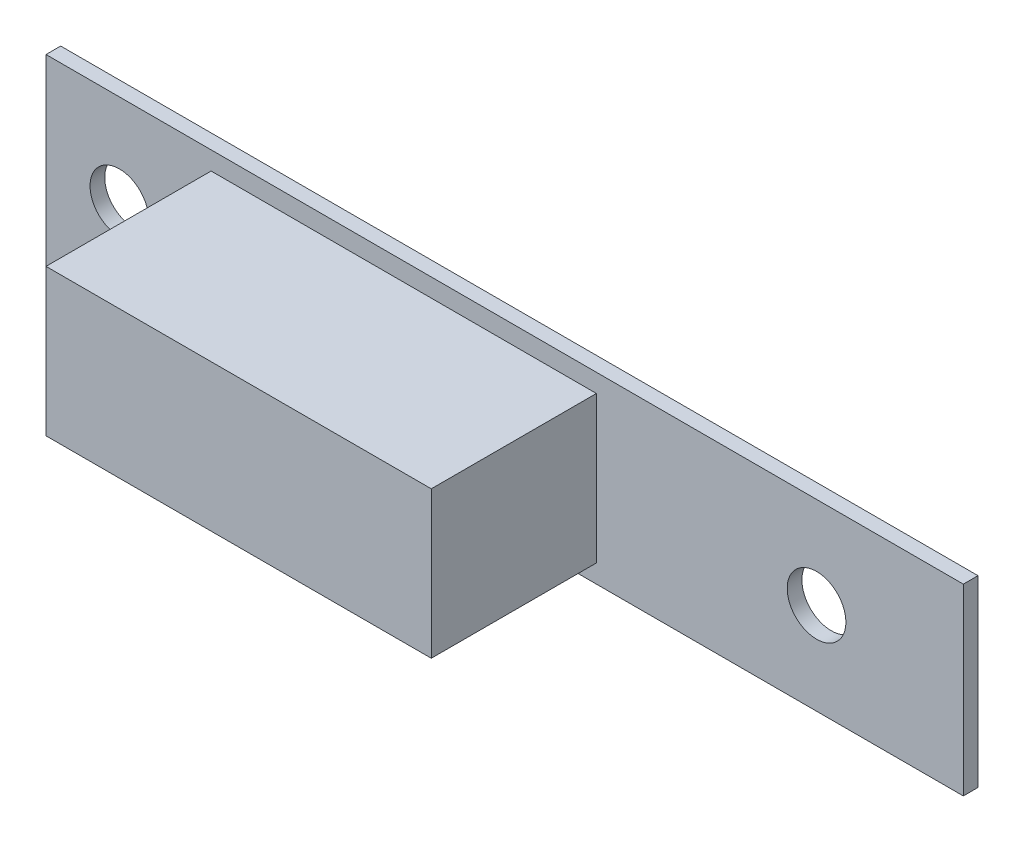
SolidWorks part; units mm, degrees
ref_plane "Front Plane" through (0, 0, 0) normal (0, 0, 1) x (1, 0, 0)
ref_plane "Top Plane" through (0, 0, 0) normal (0, 1, 0) x (1, 0, 0)
ref_plane "Right Plane" through (0, 0, 0) normal (1, 0, 0) x (0, 0, -1)
sketch "Sketch1" plane through (0, 0, 0) normal (0, 0, 1) x (1, 0, 0)
  line L0 (0, 5) -> (50000, 5) construction
  line L1 (0, 0) -> (50, 0)
  line L2 (0, 0) -> (0, 10)
  line L3 (0, 10) -> (50, 10)
  line L4 (50, 0) -> (50, 10)
  circle A0 centre (4, 5) radius 1.6
  circle A1 centre (42, 5) radius 1.6
  point P7 (0, 5)
  dimension "D3" = 3.2
  dimension "D1" = 50
  dimension "D2" = 10
  dimension "D4" = 4
  dimension "D5" = 8
extrude "Boss-Extrude1" add sketch "Sketch1" along normal blind 0.8
sketch "Sketch2" plane through (0, 0, 0.8) normal (0, 0, 1) x (1, 0, 0)
  line L0 (0, 5) -> (50000, 5) construction
  line L1 (9, 9) -> (30, 9)
  line L2 (9, 9) -> (9, 1)
  line L3 (9, 1) -> (30, 1)
  line L4 (30, 9) -> (30, 1)
  line L5 (0, 10) -> (0, 0) construction
  point P8 (0, 5)
  dimension "D1" = 8
  dimension "D2" = 21
  dimension "D3" = 9
extrude "Boss-Extrude2" add sketch "Sketch2" along normal blind 9
